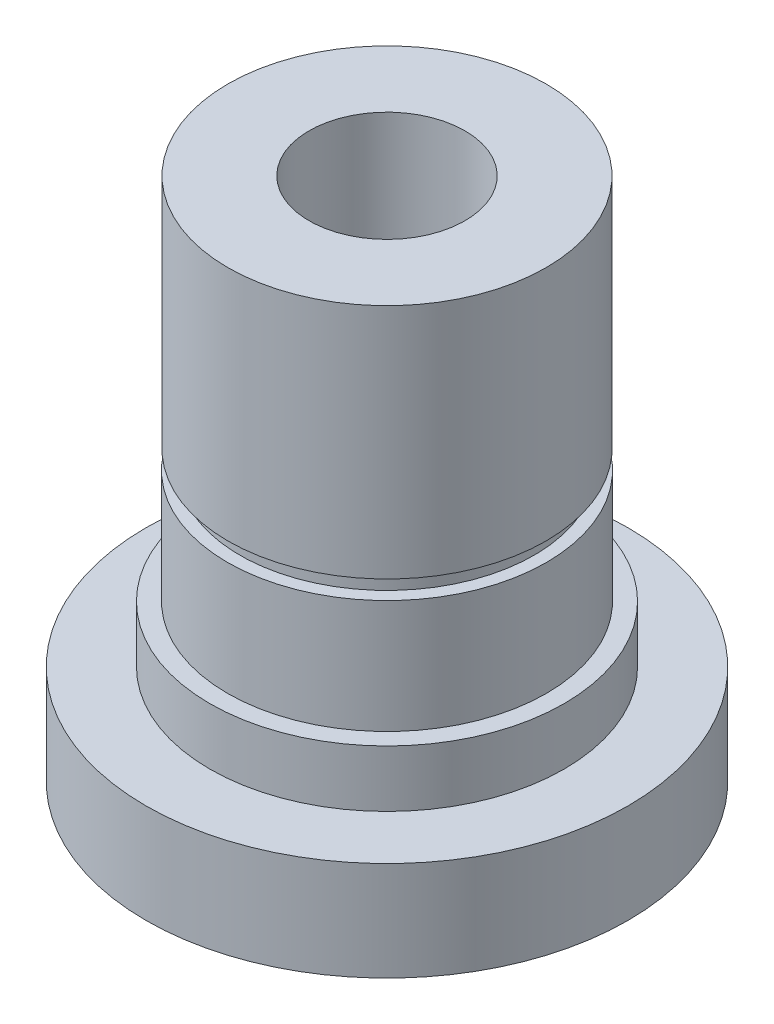
SolidWorks part; units mm, degrees
ref_plane "Front Plane" through (0, 0, 0) normal (0, 0, 1) x (1, 0, 0)
ref_plane "Top Plane" through (0, 0, 0) normal (0, 1, 0) x (1, 0, 0)
ref_plane "Right Plane" through (0, 0, 0) normal (1, 0, 0) x (0, 0, -1)
sketch "Sketch1" plane through (0, 0, 0) normal (0, 0, 1) x (1, 0, 0)
  line L0 (0, 0) -> (0, 99.6324) construction
  line L1 (-6, 0) -> (-34, 0)
  line L2 (-34, 0) -> (-34, 14)
  line L3 (-34, 14) -> (-25, 14)
  line L4 (-25, 14) -> (-25, 74)
  line L5 (-25, 74) -> (-11, 74)
  line L6 (-11, 74) -> (-11, 30)
  line L7 (-11, 30) -> (-3.25, 30)
  line L9 (-3.25, 30) -> (-3.25, 10)
  line L10 (-3.25, 10) -> (-6, 10)
  line L11 (-6, 10) -> (-6, 0)
  dimension "D1" = 50
  dimension "D2" = 60
  dimension "D3" = 14
  dimension "D4" = 22
  dimension "D5" = 68
  dimension "D6" = 44
  dimension "D7" = 12
  dimension "D8" = 10
  dimension "D9" = 6.5
revolve "Revolve1" add sketch "Sketch1" angle 360 about L0
sketch "Sketch3" plane through (0, 0, 0) normal (0, 0, 1) x (1, 0, 0)
  line L0 (0, 0) -> (0, 116.4326) construction
  line L1 (22.45, 74) -> (22.45, 40.6)
  line L2 (25, 74) -> (-25, 74) construction
  line L3 (22.45, 40.6) -> (20.75, 40.6)
  line L4 (20.75, 40.6) -> (20.75, 38)
  line L5 (20.75, 38) -> (22.5, 38)
  line L6 (22.5, 38) -> (22.5, 22)
  line L7 (22.5, 22) -> (25, 22)
  line L8 (25, 14) -> (25, 74) construction
  line L9 (25, 22) -> (25, 74)
  line L10 (25, 74) -> (22.45, 74)
  line L11 (34, 14) -> (-34, 14) construction
  dimension "D1" = 8
  dimension "D2" = 45
  dimension "D3" = 44.9
  dimension "D4" = 16
  dimension "D5" = 41.5
  dimension "D6" = 2.6
revolve "Cut-Revolve1" cut sketch "Sketch3" angle 360 about L0
